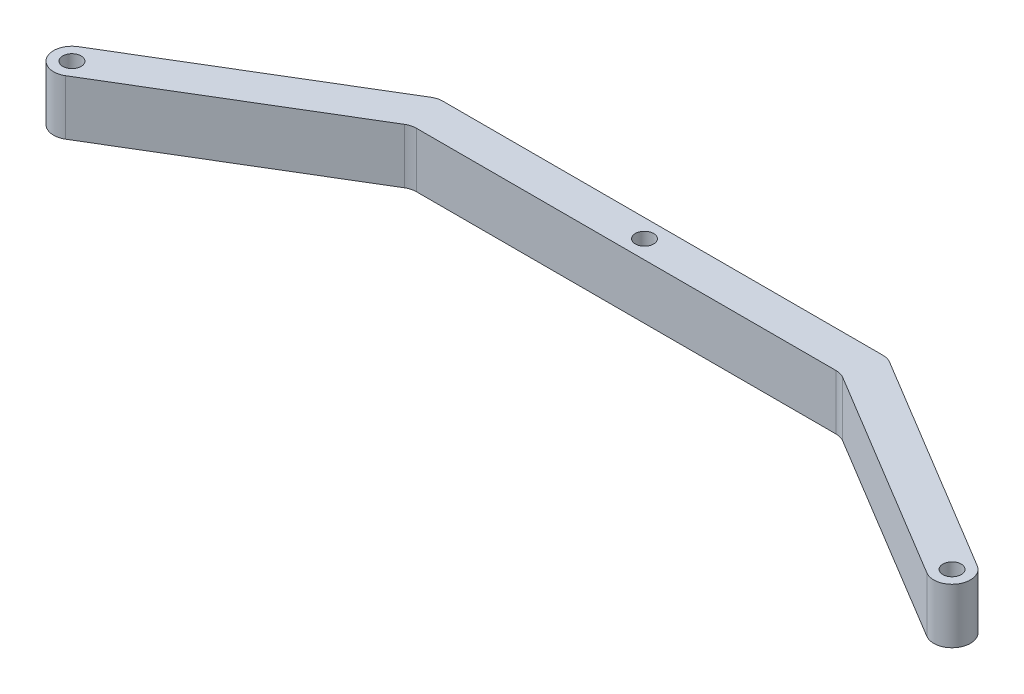
SolidWorks part; units mm, degrees
ref_plane "Front Plane" through (0, 0, 0) normal (0, 0, 1) x (1, 0, 0)
ref_plane "Top Plane" through (0, 0, 0) normal (0, 1, 0) x (1, 0, 0)
ref_plane "Right Plane" through (0, 0, 0) normal (1, 0, 0) x (0, 0, -1)
sketch "Sketch1" plane through (0, 0, 0) normal (0, 1, 0) x (1, 0, 0)
  line L0 (0, 46.2865) -> (0, -42.6147) construction
  line L1 (-55.1321, 0) -> (59.249, 0) construction
  line L2 (-59.9675, 33.9722) -> (59.9675, 33.9722)
  line L3 (-57.1904, 23.9722) -> (57.1904, 23.9722)
  line L4 (-62.5458, 33.2561) -> (-122.5783, -2.8744)
  line L5 (-59.7687, 23.2561) -> (-117.4217, -11.4423)
  line L6 (59.7687, 23.2561) -> (117.4217, -11.4423)
  line L7 (62.5458, 33.2561) -> (122.5783, -2.8744)
  arc A0 (-122.5783, -2.8744) -> (-117.4217, -11.4423) centre (-120, -7.1584) ccw
  arc A1 (122.5783, -2.8744) -> (117.4217, -11.4423) centre (120, -7.1584) cw
  circle A2 centre (-120, -7.1584) radius 2.5
  circle A3 centre (120, -7.1584) radius 2.5
  arc A4 (59.9675, 33.9722) -> (62.5458, 33.2561) centre (59.9675, 28.9722) cw
  arc A5 (-59.9675, 33.9722) -> (-62.5458, 33.2561) centre (-59.9675, 28.9722) ccw
  arc A6 (57.1904, 23.9722) -> (59.7687, 23.2561) centre (57.1904, 18.9722) cw
  arc A7 (-57.1904, 23.9722) -> (-59.7687, 23.2561) centre (-57.1904, 18.9722) ccw
  point P8 (0, 33.9722)
  point P11 (0, 23.9722)
  point P21 (61.3561, 33.9722)
  point P24 (-61.3561, 33.9722)
  point P27 (58.5789, 23.9722)
  point P30 (-58.5789, 23.9722)
  point P31 (-61.8595, 22.8897)
  point P32 (-58.5789, 23.9722)
  dimension "D1" = 120
  dimension "D2" = 5
  dimension "D3" = 5
  dimension "D4" = 10
  dimension "D5" = 10
extrude "Boss-Extrude1" add sketch "Sketch1" along normal blind 15
sketch "Sketch2" plane through (0, 15, 0) normal (0, 1, 0) x (1, 0, 0)
  line L0 (59.9675, 33.9722) -> (-59.9675, 33.9722) construction
  circle A0 centre (0, 28.9722) radius 2.5
  dimension "D1" = 5
  dimension "D2" = 5
extrude "Cut-Extrude1" cut sketch "Sketch2" against normal blind 20
